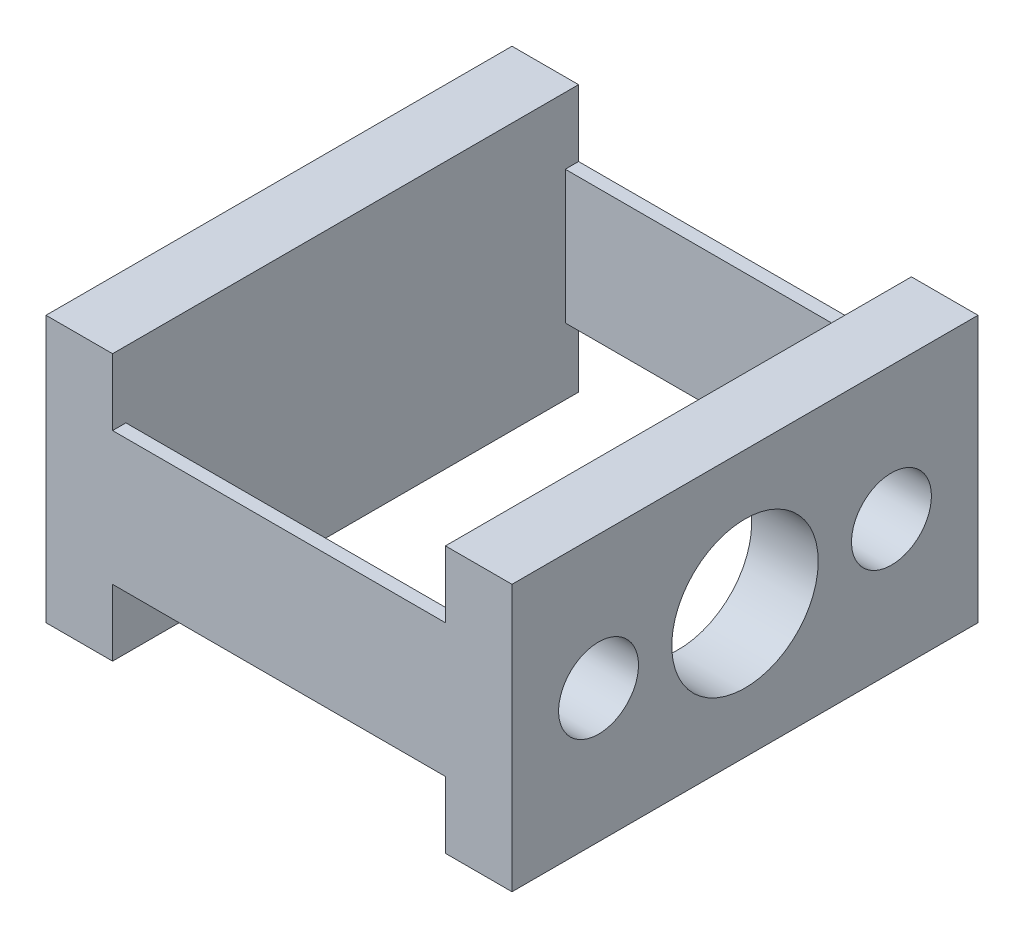
SolidWorks part; units mm, degrees
ref_plane "Front Plane" through (0, 0, 0) normal (0, 0, 1) x (1, 0, 0)
ref_plane "Top Plane" through (0, 0, 0) normal (0, 1, 0) x (1, 0, 0)
ref_plane "Right Plane" through (0, 0, 0) normal (1, 0, 0) x (0, 0, -1)
sketch "Sketch1" plane through (0, 0, 0) normal (0, 0, 1) x (1, 0, 0)
  line L0 (-17.1419, 0) -> (32.8581, 0)
  line L1 (32.8581, 0) -> (32.8581, 10)
  line L2 (32.8581, 10) -> (42.8581, 10)
  line L3 (42.8581, 10) -> (42.8581, -30)
  line L4 (42.8581, -30) -> (32.8581, -30)
  line L5 (32.8581, -30) -> (32.8581, -20)
  line L6 (32.8581, -20) -> (-17.1419, -20)
  line L7 (-17.1419, -20) -> (-17.1419, -30)
  line L8 (-17.1419, -30) -> (-27.1419, -30)
  line L9 (-27.1419, -30) -> (-27.1419, 10)
  line L10 (-27.1419, 10) -> (-17.1419, 10)
  line L11 (-17.1419, 10) -> (-17.1419, 0)
  dimension "D1" = 40
  dimension "D2" = 10
  dimension "D3" = 50
  dimension "D4" = 17.1419
  dimension "D5" = 10
extrude "Boss-Extrude1" add sketch "Sketch1" along normal blind 70
sketch "Sketch3" plane through (0, 0, 0) normal (0, 1, 0) x (1, 0, 0)
  line L0 (7.8581, 0) -> (7.8581, -70) construction
  line L1 (32.8581, 0) -> (-17.1419, 0) construction
  line L2 (32.8581, -70) -> (-17.1419, -70) construction
  line L3 (7.8581, -35) -> (32.8581, -35) construction
  line L4 (32.8581, -70) -> (32.8581, 0) construction
  line L5 (32.8581, -35) -> (-17.1419, -35) construction
  line L6 (-17.1419, -70) -> (-17.1419, 0) construction
  line L8 (-17.1419, -2) -> (32.8581, -2)
  line L9 (-17.1419, -2) -> (-17.1419, -68)
  line L10 (-17.1419, -68) -> (32.8581, -68)
  line L11 (32.8581, -2) -> (32.8581, -68)
  line L12 (-17.1419, -2) -> (32.8581, -68) construction
  line L13 (-17.1419, -68) -> (32.8581, -2) construction
  dimension "D1" = 66
extrude "Cut-Extrude1" cut sketch "Sketch3" against normal through all
sketch "Sketch4" plane through (42.8581, 0, 0) normal (1, 0, 0) x (0, 0, -1)
  line L0 (-35, 10) -> (-35, -30) construction
  line L1 (-70, 10) -> (0, 10) construction
  line L2 (-70, -30) -> (0, -30) construction
  line L3 (-70, -10) -> (-35, -10) construction
  line L4 (-70, -30) -> (-70, 10) construction
  line L5 (-35, -10) -> (0, -10) construction
  line L6 (0, -30) -> (0, 10) construction
  circle A0 centre (-35, -10) radius 11
  dimension "D1" = 22
extrude "Cut-Extrude2" cut sketch "Sketch4" against normal up to surface (10 mm away) up to face at (32.8581, -10, 35)
sketch "Sketch5" plane through (42.8581, 0, 0) normal (1, 0, 0) x (0, 0, -1)
  line L0 (-70, -10) -> (0, -10) construction
  line L1 (-70, -30) -> (-70, 10) construction
  line L2 (0, -30) -> (0, 10) construction
  line L3 (-35, 10) -> (-35, -30) construction
  line L4 (-70, 10) -> (0, 10) construction
  line L5 (-70, -30) -> (0, -30) construction
  circle A0 centre (-13, -10) radius 6
  circle A1 centre (-57, -10) radius 6
  dimension "D3" = 12
  dimension "D1" = 22
  dimension "D2" = 22
extrude "Cut-Extrude3" cut sketch "Sketch5" against normal up to surface (10 mm away) up to face at (32.8581, -10, 24)
